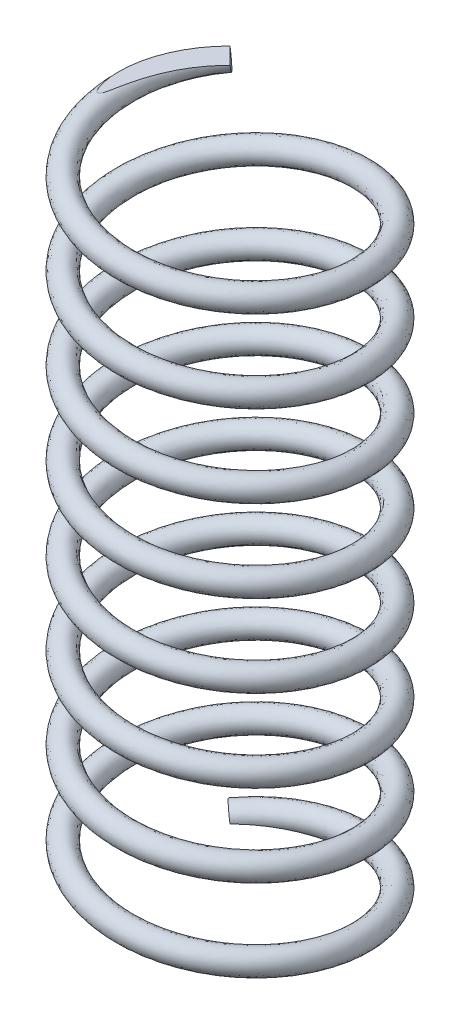
SolidWorks part; units mm, degrees
material "AISI Type 316L stainless steel"
ref_plane "Front Plane" through (0, 0, 0) normal (0, 0, 1) x (1, 0, 0)
ref_plane "Top Plane" through (0, 0, 0) normal (0, 1, 0) x (1, 0, 0)
ref_plane "Right Plane" through (0, 0, 0) normal (1, 0, 0) x (0, 0, -1)
sketch "Sketch1" plane through (0, 0, 0) normal (0, 1, 0) x (1, 0, 0)
  circle A0 centre (0, 0) radius 9.144
  dimension "D1" = 18.288
curve "Helix/Spiral1" pitch 6.35 height 50.8 turns 8
ref_plane "Plane2" through (-6.4658, 50.8, -6.4658) normal (0.7028, 0.1099, -0.7028) x (-0.6944, -0.1085, -0.7114)
sketch "Sketch2" plane through (-6.4658, 50.8, -6.4658) normal (0.7028, 0.1099, -0.7028) x (-0.6944, -0.1085, -0.7114)
  circle A0 centre (0, 0) radius 0.9144
  point P2 (-0.8936, 0.1938)
  point P3 (0, 0)
  point P4 (0, 0)
  point P6 (0, 0)
  dimension "D1" = 1.8288
sweep "Sweep1" add profiles "Sketch2" path "Helix/Spiral1"
ref_plane "Plane3" through (17.78, 0, 0) normal (1, 0, 0) x (0, 0, -1)
sketch "Sketch3" plane through (3.9222, 0.6131, -3.9222) normal (0.7028, 0.1099, -0.7028) x (-0.6938, -0.1123, -0.7114)
  line L0 (3.3782, 51.2025) -> (9.3379, 51.2025)
ref_plane "Plane4" through (0, 50.8, 0) normal (0, 1, 0) x (1, 0, 0)
sketch "Sketch4" plane through (17.78, 0, 0) normal (1, 0, 0) x (0, 0, -1)
  line L0 (11.4817, 0) -> (-11.4817, 0) construction
  line L1 (-11.4259, 0) -> (18.5989, 0)
  line L2 (-11.4259, 0) -> (-11.4259, -8.7038)
  line L3 (-11.4259, -8.7038) -> (18.5989, -8.7038)
  line L4 (18.5989, 0) -> (18.5989, -8.7038)
  line L5 (11.4817, 50.8) -> (-11.4817, 50.8) construction
  line L6 (-11.4259, 50.8) -> (22.165, 50.8)
  line L7 (-11.4259, 50.8) -> (-11.4259, 63.7121)
  line L8 (-11.4259, 63.7121) -> (22.165, 63.7121)
  line L9 (22.165, 50.8) -> (22.165, 63.7121)
extrude "Cut-Extrude2" cut sketch "Sketch4" against normal blind 35.56
sketch "Sketch5" plane through (0, 0, 0) normal (0, 1, 0) x (1, 0, 0)
  circle A0 centre (0, 0) radius 9.144
  dimension "D1" = 18.288
